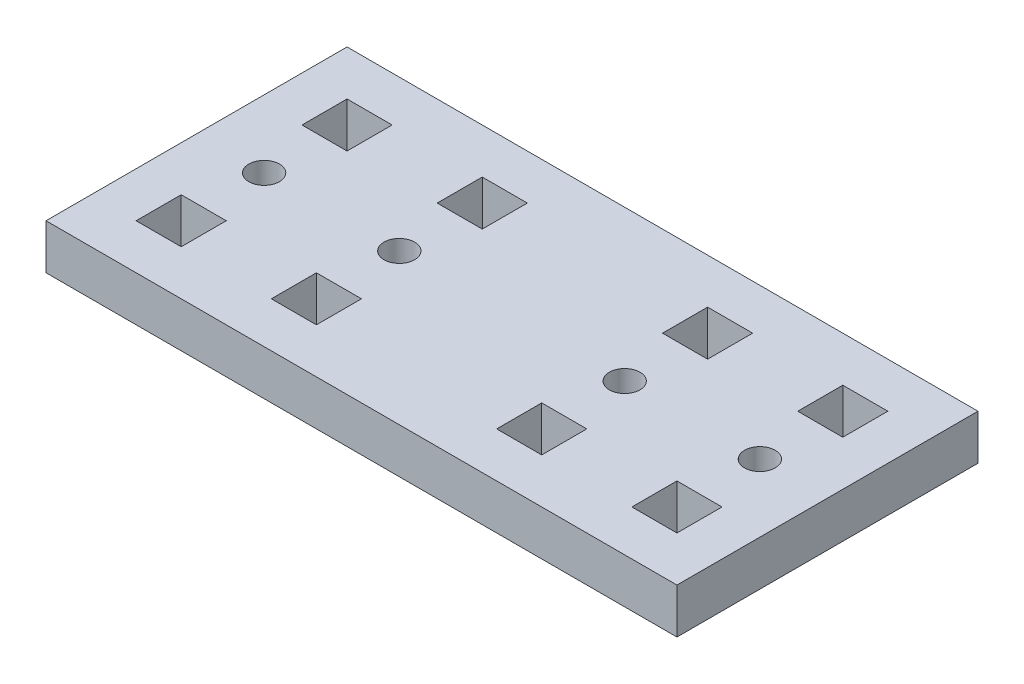
SolidWorks part; units mm, degrees
ref_plane "Front Plane" through (0, 0, 0) normal (0, 0, 1) x (1, 0, 0)
ref_plane "Top Plane" through (0, 0, 0) normal (0, 1, 0) x (1, 0, 0)
ref_plane "Right Plane" through (0, 0, 0) normal (1, 0, 0) x (0, 0, -1)
sketch "Elevator Spacer" plane through (0, 0, 0) normal (0, 1, 0) x (1, 0, 0)
  line L0 (0, 21.209) -> (0, -21.209) construction
  line L1 (-44.45, -21.209) -> (44.45, -21.209)
  line L2 (-44.45, -21.209) -> (-44.45, 21.209)
  line L3 (-44.45, 21.209) -> (44.45, 21.209)
  line L4 (44.45, -21.209) -> (44.45, 21.209)
  line L5 (-44.45, -21.209) -> (44.45, 21.209) construction
  line L6 (-44.45, 21.209) -> (44.45, -21.209) construction
  line L7 (-44.45, 0) -> (44.45, 0) construction
  line L8 (34.925, -14.859) -> (34.925, 14.859) construction
  line L9 (32.766, 0) -> (37.084, 0) construction
  line L10 (31.75, 8.509) -> (38.1, 8.509)
  line L11 (31.75, 8.509) -> (31.75, 14.859)
  line L12 (31.75, 14.859) -> (38.1, 14.859)
  line L13 (38.1, 8.509) -> (38.1, 14.859)
  line L14 (31.75, 8.509) -> (38.1, 14.859) construction
  line L15 (31.75, 14.859) -> (38.1, 8.509) construction
  line L16 (31.75, -14.859) -> (38.1, -8.509) construction
  line L17 (31.75, -8.509) -> (38.1, -14.859) construction
  line L18 (38.1, -8.509) -> (38.1, -14.859)
  line L19 (31.75, -14.859) -> (38.1, -14.859)
  line L20 (31.75, -8.509) -> (31.75, -14.859)
  line L21 (31.75, -8.509) -> (38.1, -8.509)
  line L22 (15.875, -14.859) -> (15.875, 14.859) construction
  line L23 (13.716, 0) -> (18.034, 0) construction
  line L24 (12.7, 8.509) -> (19.05, 8.509)
  line L25 (12.7, 8.509) -> (12.7, 14.859)
  line L26 (12.7, 14.859) -> (19.05, 14.859)
  line L27 (19.05, 8.509) -> (19.05, 14.859)
  line L28 (12.7, 8.509) -> (19.05, 14.859) construction
  line L29 (12.7, 14.859) -> (19.05, 8.509) construction
  line L30 (12.7, -14.859) -> (19.05, -8.509) construction
  line L31 (12.7, -8.509) -> (19.05, -14.859) construction
  line L32 (19.05, -8.509) -> (19.05, -14.859)
  line L33 (12.7, -14.859) -> (19.05, -14.859)
  line L34 (12.7, -8.509) -> (12.7, -14.859)
  line L35 (12.7, -8.509) -> (19.05, -8.509)
  line L36 (-12.7, -8.509) -> (-19.05, -14.859) construction
  line L37 (-12.7, -14.859) -> (-19.05, -8.509) construction
  line L38 (-12.7, 14.859) -> (-19.05, 8.509) construction
  line L39 (-12.7, 8.509) -> (-19.05, 14.859) construction
  line L40 (-13.716, 0) -> (-18.034, 0) construction
  line L41 (-15.875, -14.859) -> (-15.875, 14.859) construction
  line L42 (-31.75, -8.509) -> (-38.1, -14.859) construction
  line L43 (-31.75, -14.859) -> (-38.1, -8.509) construction
  line L44 (-31.75, 14.859) -> (-38.1, 8.509) construction
  line L45 (-31.75, 8.509) -> (-38.1, 14.859) construction
  line L46 (-32.766, 0) -> (-37.084, 0) construction
  line L47 (-34.925, -14.859) -> (-34.925, 14.859) construction
  line L48 (-12.7, -8.509) -> (-19.05, -8.509)
  line L49 (-12.7, -8.509) -> (-12.7, -14.859)
  line L50 (-12.7, -14.859) -> (-19.05, -14.859)
  line L51 (-19.05, -8.509) -> (-19.05, -14.859)
  line L52 (-19.05, 8.509) -> (-19.05, 14.859)
  line L53 (-12.7, 14.859) -> (-19.05, 14.859)
  line L54 (-12.7, 8.509) -> (-12.7, 14.859)
  line L55 (-12.7, 8.509) -> (-19.05, 8.509)
  line L56 (-31.75, -8.509) -> (-38.1, -8.509)
  line L57 (-31.75, -8.509) -> (-31.75, -14.859)
  line L58 (-31.75, -14.859) -> (-38.1, -14.859)
  line L59 (-38.1, -8.509) -> (-38.1, -14.859)
  line L60 (-38.1, 8.509) -> (-38.1, 14.859)
  line L61 (-31.75, 14.859) -> (-38.1, 14.859)
  line L62 (-31.75, 8.509) -> (-31.75, 14.859)
  line L63 (-31.75, 8.509) -> (-38.1, 8.509)
  circle A0 centre (34.925, 0) radius 2.159
  circle A1 centre (15.875, 0) radius 2.159
  circle A2 centre (-15.875, 0) radius 2.159
  circle A3 centre (-34.925, 0) radius 2.159
  point P0 (0, 0)
  point P12 (34.925, 11.684)
  point P25 (34.925, -11.684)
  point P28 (15.875, 11.684)
  point P41 (15.875, -11.684)
  point P70 (-15.875, -11.684)
  point P71 (-15.875, 11.684)
  point P72 (-34.925, -11.684)
  point P73 (-34.925, 11.684)
  dimension "D4" = 4.318
  dimension "D8" = 4.318
  dimension "D1" = 6.35
  dimension "D2" = 6.35
  dimension "D3" = 6.35
  dimension "D5" = 6.35
  dimension "D6" = 6.35
  dimension "D7" = 6.35
  dimension "D9" = 12.7
  dimension "D10" = 31.75
  dimension "D11" = 6.35
  dimension "D12" = 6.35
extrude "Boss-Extrude1" add sketch "Elevator Spacer" along normal blind 6.35
equation "\"Ball Diameter\"= 1.75in"
equation "\"Sheet Thickness\"= 0.25in"
equation "\"Screw Diameter\"= .17in"
equation "\"Robot Diameter\"= 14in"
equation "\"Castor Screw Diameter\"= 0.22in"
equation "\"Wheel Diameter\" = 4in"
equation "\"Nut Diameter\" = 8.4mm"
equation "\"Nut Height\" = 2.9mm"
equation "\"Screw Height\" = 0.55in"
equation "\"Pulley Diameter\" = 1in"
equation "\"Reactor Height\" = 14in"
equation "\"Elevator Height\" = 11.5in"
equation "\"Elevator Width\" = \"Ball Diameter\" + 0.25in"
equation "\"Elevator Bearing Diameter\" = sqr(2*(\"Sheet Thickness\"^2)) + 0.2in"
equation "\"Elevator Axle Endcap Diameter\" = \"Pulley Diameter\" + 0.25in"
equation "\"Elevator Axle Length\" = \"Elevator Width\" + 8*\"Sheet Thickness\""
equation "\"Elevator Clearance from Axis\" = (\"Pulley Diameter\"/2) + \"Ball Diameter\" + 0.5in"
equation "\"D1@Boss-Extrude1\"=\"Sheet Thickness\""
